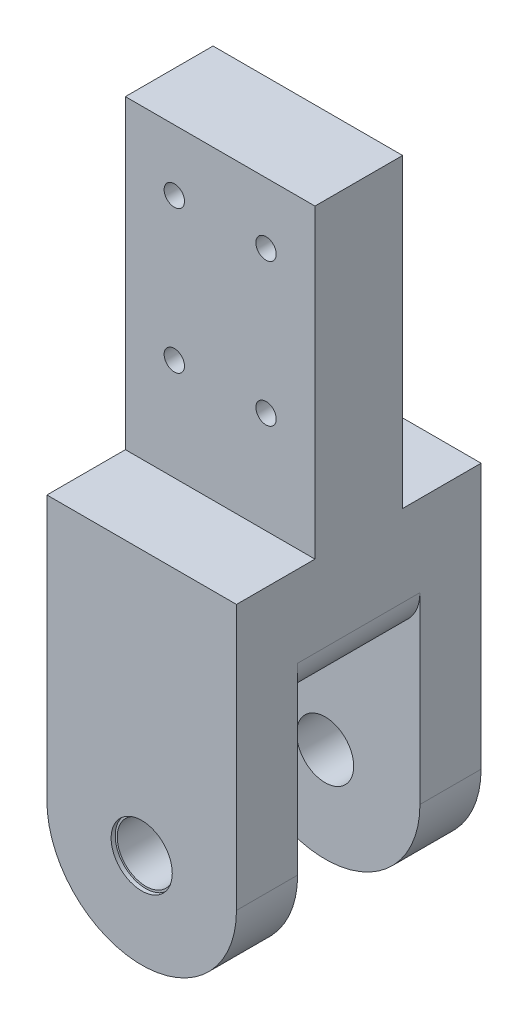
SolidWorks part; units mm, degrees
ref_plane "Front Plane" through (0, 0, 0) normal (0, 0, 1) x (1, 0, 0)
ref_plane "Top Plane" through (0, 0, 0) normal (0, 1, 0) x (1, 0, 0)
ref_plane "Right Plane" through (0, 0, 0) normal (1, 0, 0) x (0, 0, -1)
sketch "Sketch1" plane through (0, 0, 0) normal (0, 0, 1) x (1, 0, 0)
  line L0 (-23.25, 0) -> (-23.25, 140)
  line L1 (-23.25, 140) -> (23.25, 140)
  line L2 (23.25, 140) -> (23.25, 0)
  line L4 (-11.25, 125) -> (11.25, 125) construction
  line L5 (-11.25, 125) -> (-11.25, 90) construction
  line L6 (-11.25, 90) -> (11.25, 90) construction
  line L7 (11.25, 125) -> (11.25, 90) construction
  circle A0 centre (0, 0) radius 7
  arc A1 (-23.25, 0) -> (23.25, 0) centre (0, 0) ccw
  circle A2 centre (-11.25, 125) radius 2.5
  circle A3 centre (11.25, 125) radius 2.5
  circle A4 centre (11.25, 90) radius 2.5
  circle A5 centre (-11.25, 90) radius 2.5
  point P13 (0, 90)
  dimension "D1" = 14
  dimension "D4" = 5
  dimension "D2" = 46.5
  dimension "D3" = 140
  dimension "D5" = 35
  dimension "D6" = 15
  dimension "D7" = 22.5
extrude "Boss-Extrude1" add sketch "Sketch1" along normal mid plane 60
sketch "Sketch2" plane through (23.25, 0, 0) normal (1, 0, 0) x (0, 0, -1)
  line L0 (-30, -23.25) -> (30, -23.25) construction
  line L1 (-15, 35) -> (15, 35)
  line L2 (-15, 35) -> (-15, -23.25)
  line L3 (-15, -23.25) -> (15, -23.25)
  line L4 (15, 35) -> (15, -23.25)
  line L5 (-30, 0) -> (30, 0) construction
  point P8 (0, 0)
  point P9 (0, 35)
  dimension "D1" = 30
  dimension "D2" = 35
extrude "Cut-Extrude1" cut sketch "Sketch2" against normal through all
sketch "Sketch3" plane through (0, 0, 30) normal (0, 0, 1) x (1, 0, 0)
  circle A0 centre (0, 0) radius 7.5
  dimension "D1" = 15
extrude "Cut-Extrude2" cut sketch "Sketch3" against normal blind 1
sketch "Sketch4" plane through (0, 0, -30) normal (0, 0, -1) x (-1, 0, 0)
  circle A0 centre (0, 0) radius 7.5
  dimension "D1" = 15
extrude "Cut-Extrude3" cut sketch "Sketch4" against normal blind 1
sketch "Sketch6" plane through (23.25, 0, 0) normal (1, 0, 0) x (0, 0, -1)
  line L1 (-30, 140) -> (-12.7, 140)
  line L2 (-30, 140) -> (-30, 65)
  line L3 (-30, 65) -> (-12.7, 65)
  line L4 (-12.7, 140) -> (-12.7, 65)
  line L5 (30, 140) -> (12.7, 140)
  line L6 (30, 140) -> (30, 65)
  line L7 (30, 65) -> (12.7, 65)
  line L8 (12.7, 140) -> (12.7, 65)
  dimension "D1" = 25.4
  dimension "D2" = 75
extrude "Cut-Extrude4" cut sketch "Sketch6" against normal through all
sketch "Sketch7" plane through (0, 65, 0) normal (0, 1, 0) x (1, 0, 0)
  line L5 (23.25, -12.7) -> (23.25, 12.7) construction
  line L6 (-23.25, 12.7) -> (23.25, 12.7)
  line L11 (-23.25, 12.7) -> (-23.25, 10.75)
  line L12 (-23.25, 10.75) -> (23.25, 10.75)
  line L14 (23.25, 12.7) -> (23.25, 10.75)
  line L15 (-23.25, -12.7) -> (-23.25, 12.7) construction
  line L16 (23.25, -12.7) -> (-23.25, -12.7)
  line L17 (23.25, -12.7) -> (23.25, -10.75)
  line L18 (23.25, -10.75) -> (-23.25, -10.75)
  line L19 (-23.25, -12.7) -> (-23.25, -10.75)
  dimension "D1" = 21.5
extrude "Cut-Extrude5" cut sketch "Sketch7" along normal through all
fillet "Fillet1" radius 10 2 edges at (23.25, 35, 0) (-23.25, 35, 0)
